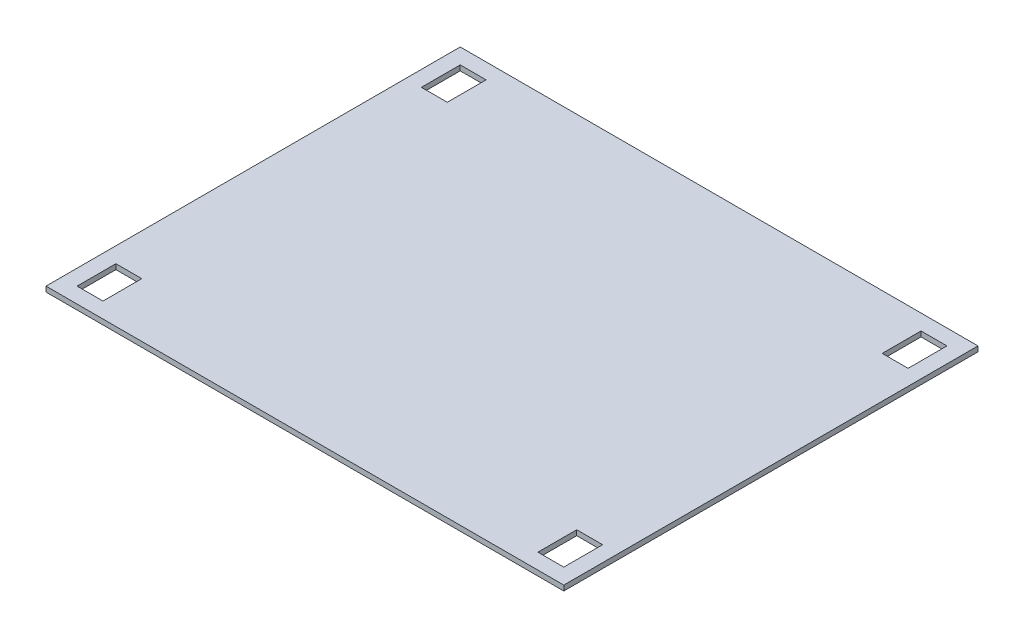
SolidWorks part; units mm, degrees
ref_plane "Front Plane" through (0, 0, 0) normal (0, 0, 1) x (1, 0, 0)
ref_plane "Top Plane" through (0, 0, 0) normal (0, 1, 0) x (1, 0, 0)
ref_plane "Right Plane" through (0, 0, 0) normal (1, 0, 0) x (0, 0, -1)
sketch "Sketch1" plane through (0, 0, 0) normal (0, 1, 0) x (1, 0, 0)
  line L1 (-63.5, 50.8) -> (63.5, 50.8)
  line L2 (-63.5, 50.8) -> (-63.5, -50.8)
  line L3 (-63.5, -50.8) -> (63.5, -50.8)
  line L4 (63.5, 50.8) -> (63.5, -50.8)
  dimension "D1" = 127
  dimension "D2" = 101.6
  dimension "D3" = 50.8
  dimension "D4" = 63.5
extrude "Boss-Extrude1" add sketch "Sketch1" along normal blind 1.27
sketch "Sketch2" plane through (0, 1.27, 0) normal (0, 1, 0) x (1, 0, 0)
  line L0 (-63.5, 50.8) -> (-63.5, -50.8) construction
  line L1 (-59.69, 46.99) -> (-53.34, 46.99)
  line L2 (-59.69, 46.99) -> (-59.69, 37.465)
  line L3 (-59.69, 37.465) -> (-53.34, 37.465)
  line L4 (-53.34, 46.99) -> (-53.34, 37.465)
  line L5 (63.5, 50.8) -> (-63.5, 50.8) construction
  line L6 (0, -0.6985) -> (0, 0.6985) construction
  line L7 (53.34, 46.99) -> (53.34, 37.465)
  line L8 (59.69, 46.99) -> (53.34, 46.99)
  line L9 (59.69, 46.99) -> (59.69, 37.465)
  line L10 (59.69, 37.465) -> (53.34, 37.465)
  line L11 (-0.6985, 0) -> (0.6985, 0) construction
  line L12 (59.69, -37.465) -> (53.34, -37.465)
  line L13 (53.34, -46.99) -> (53.34, -37.465)
  line L14 (59.69, -46.99) -> (53.34, -46.99)
  line L15 (59.69, -46.99) -> (59.69, -37.465)
  line L16 (-53.34, -46.99) -> (-53.34, -37.465)
  line L17 (-59.69, -46.99) -> (-53.34, -46.99)
  line L18 (-59.69, -46.99) -> (-59.69, -37.465)
  line L19 (-59.69, -37.465) -> (-53.34, -37.465)
  point P4 (-59.69, 42.2275)
  dimension "D1" = 6.35
  dimension "D2" = 9.525
  dimension "D3" = 3.81
  dimension "D4" = 3.81
extrude "Cut-Extrude1" cut sketch "Sketch2" against normal up to next
